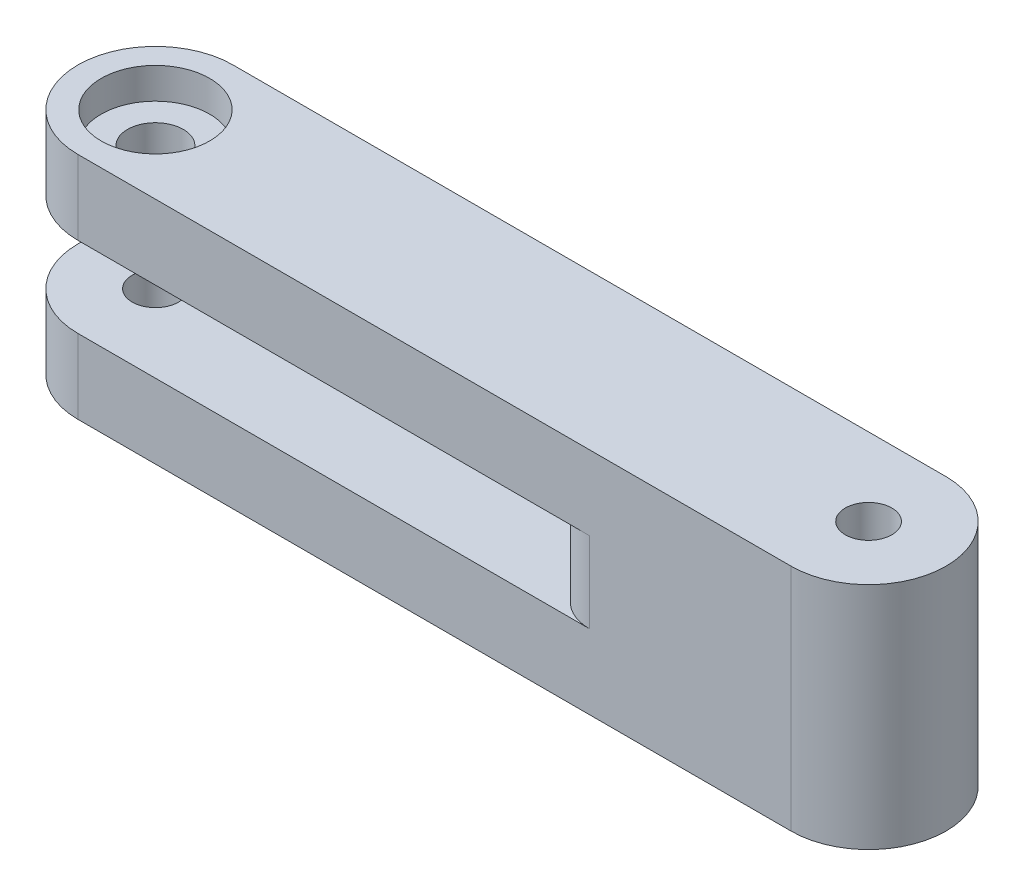
SolidWorks part; units mm, degrees
ref_plane "Front Plane" through (0, 0, 0) normal (0, 0, 1) x (1, 0, 0)
ref_plane "Top Plane" through (0, 0, 0) normal (0, 1, 0) x (1, 0, 0)
ref_plane "Right Plane" through (0, 0, 0) normal (1, 0, 0) x (0, 0, -1)
sketch "Sketch1" plane through (0, 0, 0) normal (0, 1, 0) x (1, 0, 0)
  line L0 (-29.21, 0) -> (29.21, 0) construction
  line L1 (-29.21, 6.35) -> (29.21, 6.35)
  line L2 (-29.21, -6.35) -> (29.21, -6.35)
  arc A0 (-29.21, 6.35) -> (-29.21, -6.35) centre (-29.21, 0) ccw
  arc A1 (29.21, -6.35) -> (29.21, 6.35) centre (29.21, 0) ccw
  circle A2 centre (-29.21, 0) radius 2.286
  circle A3 centre (29.21, 0) radius 1.905
  point P2 (0, 0)
  dimension "D3" = 4.572
  dimension "D4" = 3.81
  dimension "D1" = 58.42
  dimension "D2" = 12.7
extrude "Boss-Extrude1" add sketch "Sketch1" along normal blind 18.796
sketch "Sketch2" plane through (0, 0, 6.35) normal (0, 0, 1) x (1, 0, 0)
  line L0 (-29.21, 18.796) -> (29.21, 18.796) construction
  line L1 (-35.56, 12.7) -> (8.89, 12.7)
  line L2 (-35.56, 12.7) -> (-35.56, 6.096)
  line L3 (-35.56, 6.096) -> (8.89, 6.096)
  line L4 (8.89, 12.7) -> (8.89, 6.096)
  line L5 (-35.56, 18.796) -> (-35.56, 0) construction
  dimension "D1" = 6.096
  dimension "D2" = 6.604
  dimension "D3" = 44.45
extrude "Cut-Extrude1" cut sketch "Sketch2" against normal through all
sketch "Sketch3" plane through (0, 18.796, 0) normal (0, 1, 0) x (1, 0, 0)
  circle A0 centre (-29.21, 0) radius 4.445
  dimension "D1" = 8.89
extrude "Cut-Extrude2" cut sketch "Sketch3" against normal blind 2.54
sketch "Sketch4" plane through (0, 6.096, 0) normal (0, 1, 0) x (1, 0, 0)
  circle A0 centre (-29.21, 0) radius 1.905
  circle A1 centre (-29.21, 0) radius 2.286
  dimension "D1" = 3.81
extrude "Boss-Extrude2" add sketch "Sketch4" against normal up to surface (6.096 mm away) up to face at (0, 0, 0)
fillet "Fillet1" radius 3.81 2 edges at (8.89, 9.398, -6.35) (8.89, 9.398, 6.35)
